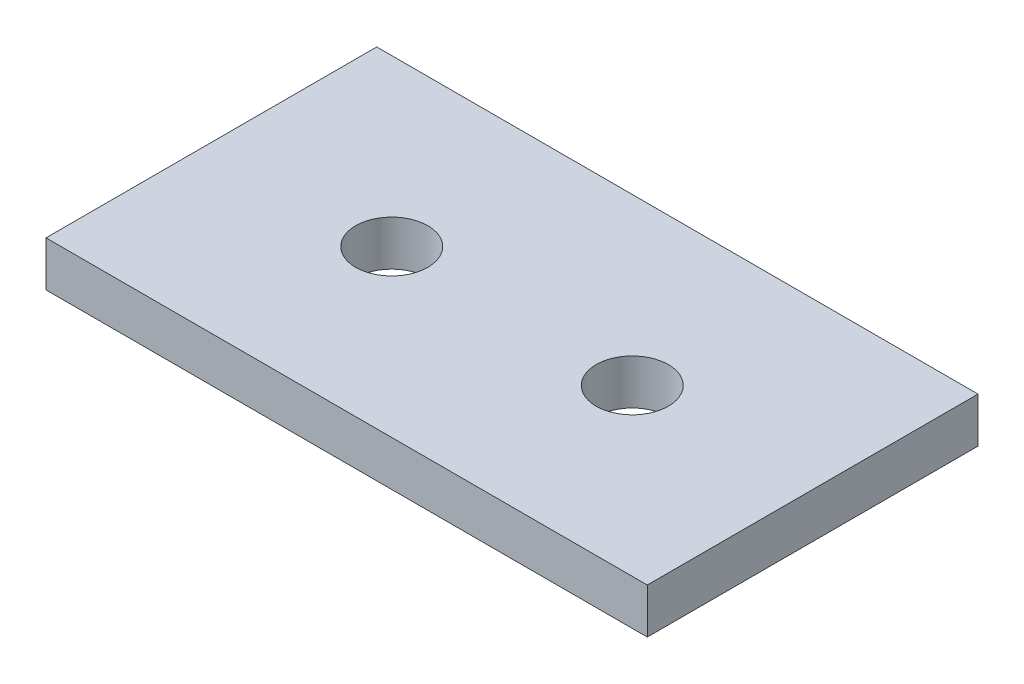
SolidWorks part; units mm, degrees
ref_plane "Front Plane" through (0, 0, 0) normal (0, 0, 1) x (1, 0, 0)
ref_plane "Top Plane" through (0, 0, 0) normal (0, 1, 0) x (1, 0, 0)
ref_plane "Right Plane" through (0, 0, 0) normal (1, 0, 0) x (0, 0, -1)
sketch "Sketch1" plane through (0, 0, 0) normal (0, 1, 0) x (1, 0, 0)
  line L0 (-20, 5.5) -> (0, 5.5)
  line L1 (0, 5.5) -> (0, -5.5)
  line L2 (0, -5.5) -> (-20, -5.5)
  line L3 (-20, -5.5) -> (-20, 5.5)
extrude "Boss-Extrude1" add sketch "Sketch1" against normal blind 1.5
sketch "Sketch2" plane through (0, 0, 0) normal (0, 1, 0) x (1, 0, 0)
  circle A0 centre (-6, 0) radius 1.2
  circle A1 centre (-14, 0) radius 1.2
extrude "Cut-Extrude1" cut sketch "Sketch2" against normal blind 1.5
